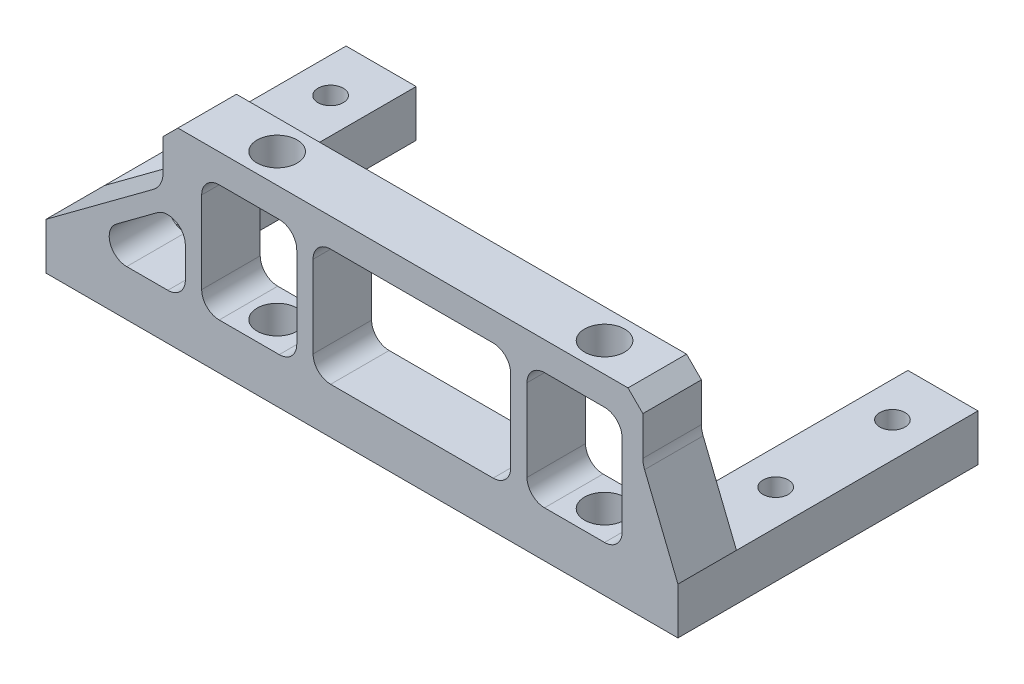
SolidWorks part; units mm, degrees
ref_plane "Front Plane" through (0, 0, 0) normal (0, 0, 1) x (1, 0, 0)
ref_plane "Top Plane" through (0, 0, 0) normal (0, 1, 0) x (1, 0, 0)
ref_plane "Right Plane" through (0, 0, 0) normal (1, 0, 0) x (0, 0, -1)
sketch "Sketch1" plane through (0, 0, 0) normal (0, 0, 1) x (1, 0, 0)
  line L0 (0, 0) -> (54.0258, 0)
  line L1 (54.0258, 0) -> (54.0258, 3.9878)
  line L2 (54.0258, 3.9878) -> (51.1766, 11.0383)
  line L3 (51.0286, 11.7997) -> (51.0286, 15.113)
  line L4 (11.2776, 16.383) -> (10.0076, 15.113)
  line L5 (49.7586, 16.383) -> (11.2776, 16.383)
  line L6 (51.0286, 15.113) -> (49.7586, 16.383)
  line L7 (10.0076, 15.113) -> (10.0076, 12.4279)
  line L8 (9.1855, 10.7953) -> (0, 3.9878)
  line L9 (0, 3.9878) -> (0, 0)
  arc A0 (51.1766, 11.0383) -> (51.0286, 11.7997) centre (53.0606, 11.7997) cw
  arc A1 (10.0076, 12.4279) -> (9.1855, 10.7953) centre (7.9756, 12.4279) cw
  point P8 (51.0286, 16.383)
  point P12 (10.0076, 16.383)
  point P16 (51.0286, 11.4046)
  dimension "D8" = 2.032
  dimension "D1" = 54.0258
  dimension "D2" = 16.383
  dimension "D3" = 41.021
  dimension "D4" = 3.9878
  dimension "D5" = 3.9878
  dimension "D6" = 2.9972
  dimension "D7" = 4.9784
extrude "Boss-Extrude1" add sketch "Sketch1" against normal blind 25.654
sketch "Sketch2" plane through (54.0258, 0, 0) normal (1, 0, 0) x (0, 0, -1)
  line L0 (25.654, 3.9878) -> (0, 3.9878) construction
  line L1 (25.654, 3.9878) -> (5.0038, 3.9878)
  line L2 (5.0038, 16.383) -> (5.0038, 3.9878)
  line L3 (0, 3.9878) -> (0, 11.0383) construction
  line L4 (25.654, 16.383) -> (0, 16.383) construction
  line L5 (25.654, 16.383) -> (5.0038, 16.383)
  line L6 (25.654, 11.7997) -> (25.654, 15.113) construction
  line L7 (25.654, 3.9878) -> (25.654, 16.383)
  dimension "D1" = 5.0038
extrude "Cut-Extrude1" cut sketch "Sketch2" against normal through all
sketch "Sketch3" plane through (0, 3.9878, 0) normal (0, 1, 0) x (1, 0, 0)
  line L0 (5.9944, 25.654) -> (5.9944, 5.0038)
  line L1 (48.0314, 5.0038) -> (48.0314, 25.654)
  line L4 (54.0258, 5.0038) -> (54.0258, 25.654)
  line L5 (54.0258, 25.654) -> (0, 25.654)
  line L6 (0, 25.654) -> (0, 5.0038)
  line L7 (0, 5.0038) -> (54.0258, 5.0038)
  line L8 (54.0258, 5.0038) -> (54.0258, 25.654) construction
  line L9 (48.0314, 25.654) -> (5.9944, 25.654)
  line L10 (0, 25.654) -> (0, 5.0038) construction
  line L11 (5.9944, 5.0038) -> (48.0314, 5.0038)
  dimension "D1" = 0
  dimension "D2" = 5.9944
extrude "Cut-Extrude2" cut sketch "Sketch3" against normal through all
sketch "Sketch4" plane through (0, 0, 0) normal (0, 0, 1) x (1, 0, 0)
  line L2 (0, 3.937) -> (54.0258, 3.937)
  line L3 (6.902, 3.937) -> (10.414, 3.937)
  line L5 (49.7586, 13.9446) -> (11.2776, 13.9446)
  line L6 (47.752, 13.9446) -> (42.6212, 13.9446)
  line L8 (49.2506, 11.7997) -> (49.2506, 15.113)
  line L9 (49.2506, 5.4356) -> (49.2506, 12.446)
  line L11 (13.3096, 15.113) -> (13.3096, 12.4279)
  line L12 (13.3096, 12.446) -> (13.3096, 5.4356)
  line L13 (11.9126, 8.0384) -> (11.9126, 5.4356)
  line L14 (10.0476, 9.6321) -> (0.8621, 2.8246)
  line L15 (9.5217, 9.2424) -> (6.0097, 6.6396)
  line L16 (11.9126, 13.9446) -> (11.9126, 3.937) construction
  line L17 (21.4376, 12.446) -> (21.4376, 5.4356)
  line L18 (22.8346, 12.446) -> (22.8346, 5.4356)
  line L19 (41.1226, 5.4356) -> (41.1226, 12.446)
  line L20 (39.7256, 5.4356) -> (39.7256, 12.446)
  line L21 (14.8082, 3.937) -> (19.939, 3.937)
  line L22 (24.3332, 3.937) -> (38.227, 3.937)
  line L23 (42.6212, 3.937) -> (47.752, 3.937)
  line L24 (38.227, 13.9446) -> (24.3332, 13.9446)
  line L25 (19.939, 13.9446) -> (14.8082, 13.9446)
  line L26 (49.2506, 3.937) -> (49.2506, 13.9446) construction
  line L27 (41.1226, 3.937) -> (41.1226, 13.9446) construction
  line L28 (22.8346, 13.9446) -> (22.8346, 3.937) construction
  line L29 (39.7256, 3.937) -> (39.7256, 13.9446) construction
  line L30 (13.3096, 13.9446) -> (13.3096, 3.937) construction
  line L31 (21.4376, 13.9446) -> (21.4376, 3.937) construction
  arc A0 (47.752, 13.9446) -> (49.2506, 12.446) centre (47.752, 12.446) cw
  arc A1 (49.2506, 5.4356) -> (47.752, 3.937) centre (47.752, 5.4356) cw
  arc A2 (42.6212, 3.937) -> (41.1226, 5.4356) centre (42.6212, 5.4356) cw
  arc A3 (41.1226, 12.446) -> (42.6212, 13.9446) centre (42.6212, 12.446) cw
  arc A4 (22.8346, 12.446) -> (24.3332, 13.9446) centre (24.3332, 12.446) cw
  arc A5 (38.227, 13.9446) -> (39.7256, 12.446) centre (38.227, 12.446) cw
  arc A6 (39.7256, 5.4356) -> (38.227, 3.937) centre (38.227, 5.4356) cw
  arc A7 (24.3332, 3.937) -> (22.8346, 5.4356) centre (24.3332, 5.4356) cw
  arc A8 (13.3096, 5.4356) -> (14.8082, 3.937) centre (14.8082, 5.4356) ccw
  arc A9 (19.939, 3.937) -> (21.4376, 5.4356) centre (19.939, 5.4356) ccw
  arc A10 (21.4376, 12.446) -> (19.939, 13.9446) centre (19.939, 12.446) ccw
  arc A11 (14.8082, 13.9446) -> (13.3096, 12.446) centre (14.8082, 12.446) ccw
  arc A12 (9.5217, 9.2424) -> (11.9126, 8.0384) centre (10.414, 8.0384) cw
  arc A13 (11.9126, 5.4356) -> (10.414, 3.937) centre (10.414, 5.4356) cw
  arc A14 (6.902, 3.937) -> (6.0097, 6.6396) centre (6.902, 5.4356) cw
  dimension "D11" = 1.4986
  dimension "D1" = 3.937
  dimension "D2" = 2.4384
  dimension "D3" = 1.778
  dimension "D4" = 3.302
  dimension "D5" = 1.4478
  dimension "D6" = 1.397
  dimension "D7" = 8.128
  dimension "D8" = 1.397
  dimension "D9" = 8.128
  dimension "D10" = 1.397
extrude "Cut-Extrude3" cut sketch "Sketch4" against normal blind 5.08
sketch "Sketch5" plane through (0, 3.9878, 0) normal (0, 1, 0) x (1, 0, 0)
  line L0 (48.0314, 25.654) -> (54.0258, 25.654) construction
  line L1 (48.0314, 25.654) -> (54.0258, 25.654) construction
  line L2 (5.9944, 25.654) -> (48.0314, 25.654) construction
  line L3 (27.0129, 25.654) -> (27.0129, 11.3538) construction
  circle A0 centre (51.0286, 21.336) radius 1.0795
  circle A1 centre (51.0286, 11.3538) radius 1.0795
  circle A2 centre (2.9972, 11.3538) radius 1.0795
  circle A3 centre (2.9972, 21.336) radius 1.0795
  point P6 (51.0286, 25.654)
  point P7 (51.0286, 25.654)
  dimension "D1" = 2.159
  dimension "D2" = 2.159
  dimension "D3" = 4.318
  dimension "D4" = 0
  dimension "D5" = 0
  dimension "D6" = 9.9822
extrude "Cut-Extrude4" cut sketch "Sketch5" against normal through all
sketch "Sketch6" plane through (0, 0, 0) normal (0, -1, 0) x (1, 0, 0)
  line L0 (27.0129, 0) -> (27.0129, -5.0038) construction
  line L1 (0, 0) -> (54.0258, 0) construction
  line L2 (5.9944, -5.0038) -> (48.0314, -5.0038) construction
  line L3 (27.0129, -2.5019) -> (56.1106, -2.5019) construction
  line L4 (27.0129, -2.5019) -> (-2.3785, -2.5019) construction
  line L5 (54.0258, -25.654) -> (54.0258, 0) construction
  circle A0 centre (45.2501, -2.5019) radius 1.7145
  circle A1 centre (17.2593, -2.5019) radius 1.7145
  dimension "D1" = 3.429
  dimension "D2" = 3.429
  dimension "D3" = 8.7757
  dimension "D4" = 27.9908
extrude "Cut-Extrude5" cut sketch "Sketch6" against normal through all
